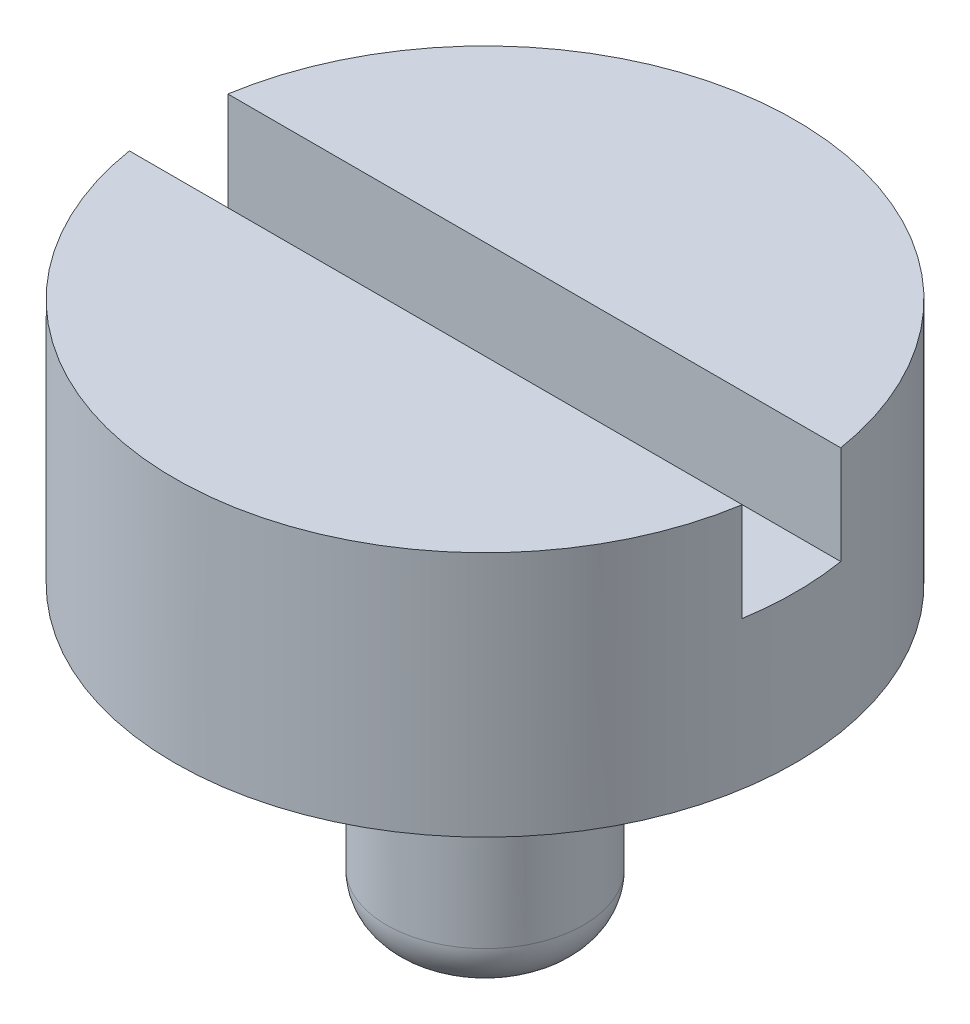
SolidWorks part; units mm, degrees
ref_plane "Front" through (0, 0, 0) normal (0, 0, 1) x (1, 0, 0)
ref_plane "Top" through (0, 0, 0) normal (0, 1, 0) x (1, 0, 0)
ref_plane "Right" through (0, 0, 0) normal (1, 0, 0) x (0, 0, -1)
sketch "Sketch1" plane through (0, 0, 0) normal (0, 1, 0) x (1, 0, 0)
  circle A0 centre (0, 0) radius 2.54
  dimension "D1" = 5.08
extrude "Boss-Extrude1" add sketch "Sketch1" along normal blind 7.62
sketch "Sketch2" plane through (0, 7.62, 0) normal (0, 1, 0) x (1, 0, 0)
  circle A0 centre (0, 0) radius 8.001
  dimension "D1" = 16.002
extrude "Boss-Extrude2" add sketch "Sketch2" along normal blind 6.35
fillet "Fillet1" radius 1.27 1 edges at (0, 0, 2.54)
sketch "Sketch3" plane through (0, 0, 0) normal (1, 0, 0) x (0, 0, -1)
  line L0 (0, 0) -> (0, 13.97) construction
  line L1 (8.001, 13.97) -> (-8.001, 13.97) construction
  line L3 (1.27, 11.43) -> (-1.27, 11.43)
  line L4 (1.27, 11.43) -> (1.27, 13.97)
  line L5 (1.27, 13.97) -> (-1.27, 13.97)
  line L6 (-1.27, 11.43) -> (-1.27, 13.97)
  line L7 (1.27, 11.43) -> (-1.27, 13.97) construction
  line L8 (1.27, 13.97) -> (-1.27, 11.43) construction
  point P5 (0, 12.7)
  dimension "D1" = 2.54
  dimension "D2" = 2.54
extrude "Cut-Extrude1" cut sketch "Sketch3" against normal mid plane 127 contours L4 L3 L6 L5
